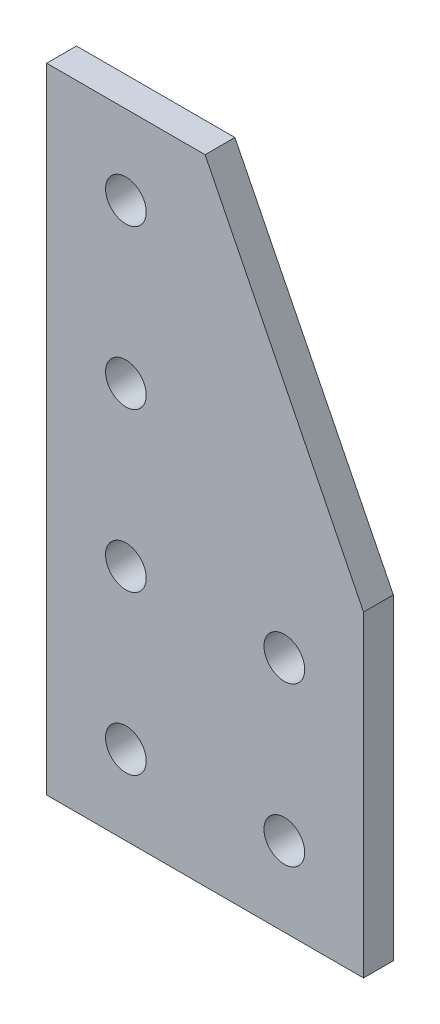
SolidWorks part; units mm, degrees
ref_plane "Front Plane" through (0, 0, 0) normal (0, 0, 1) x (1, 0, 0)
ref_plane "Top Plane" through (0, 0, 0) normal (0, 1, 0) x (1, 0, 0)
ref_plane "Right Plane" through (0, 0, 0) normal (1, 0, 0) x (0, 0, -1)
sketch "Sketch1" plane through (0, 0, 0) normal (0, 0, 1) x (1, 0, 0)
  line L0 (25.4, -50.8) -> (-25.4, -50.8) construction
  line L1 (-25.4, -50.8) -> (-25.4, 50.8) construction
  line L2 (-25.4, 50.8) -> (0, 50.8) construction
  line L3 (-15.9639, -38.1) -> (-9.4361, -38.1) construction
  line L4 (0, -50.8) -> (0, -38.1) construction
  point P0 (-25.4, 0)
  point P10 (-12.7, -38.1)
  point P11 (12.7, -38.1)
  dimension "Length" = 101.6
  dimension "For Rail Height" = 25.4
  dimension "Width" = 50.8
  dimension "Hole Dia" = 6.5278
  dimension "Hole to Bottom" = 12.7
  dimension "Hole Spacing" = 25.4
sketch "Sketch2" plane through (0, 0, 0) normal (1, 0, 0) x (0, 0, -1)
  line L0 (2.3876, 0) -> (-2.3876, 0) construction
  point P3 (0, 0)
  dimension "Thickness" = 4.7752
sketch "Sketch3" plane through (0, 0, 0) normal (0, 0, 1) x (1, 0, 0)
  line L0 (0, 50.8) -> (-25.4, 50.8)
  line L1 (-25.4, 50.8) -> (-25.4, -50.8)
  line L2 (-25.4, -50.8) -> (25.4, -50.8)
  line L3 (25.4, -50.8) -> (25.4, 0)
  line L4 (25.4, 0) -> (0, 50.8)
extrude "Boss-Extrude1" add sketch "Sketch3" along normal up to vertex (2.3876 mm away) and the other way up to vertex (2.3876 mm away)
sketch "Sketch4" plane through (0, 0, 2.3876) normal (0, 0, 1) x (1, 0, 0)
  line L0 (-12.7, -38.1) -> (12.7, -38.1) construction
  line L1 (-12.7, -38.1) -> (-12.7, -12.7) construction
  circle A0 centre (-12.7, -38.1) radius 3.2639
  circle A1 centre (12.7, -38.1) radius 3.2639
  circle A2 centre (12.7, -12.7) radius 3.2639
  circle A3 centre (12.7, 12.7) radius 3.2639 [skipped]
  circle A4 centre (12.7, 38.1) radius 3.2639 [skipped]
  circle A5 centre (-12.7, -12.7) radius 3.2639
  circle A6 centre (-12.7, 12.7) radius 3.2639
  circle A7 centre (-12.7, 38.1) radius 3.2639
  dimension "D3" = 90
  dimension "D4" = 25.4
  dimension "D5" = 25.4
  dimension "D1" = 2
  dimension "D2" = 4
extrude "Cut-Extrude1" cut sketch "Sketch4" against normal through all
equation "\"D5@Sketch4\"=\"Hole Spacing@Sketch1\""
equation "\"D4@Sketch4\"=\"Hole Spacing@Sketch1\""
